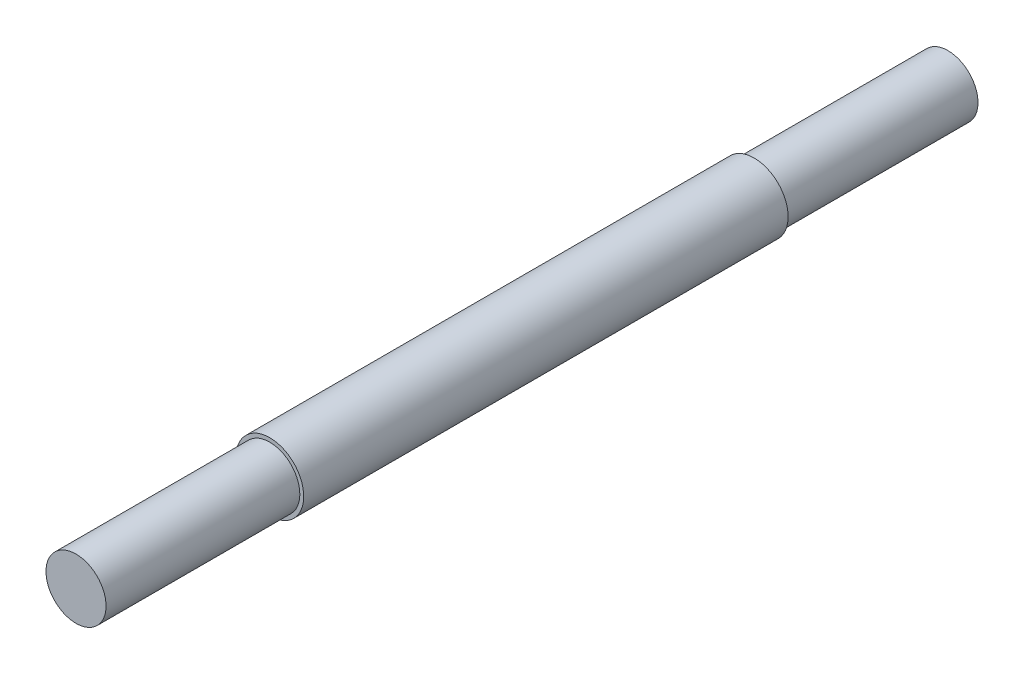
SolidWorks part; units mm, degrees
material "AISI 316 Annealed Stainless Steel Bar (SS)"
ref_plane "Front Plane" through (0, 0, 0) normal (0, 0, 1) x (1, 0, 0)
ref_plane "Top Plane" through (0, 0, 0) normal (0, 1, 0) x (1, 0, 0)
ref_plane "Right Plane" through (0, 0, 0) normal (1, 0, 0) x (0, 0, -1)
sketch "Sketch1" plane through (0, 0, 0) normal (1, 0, 0) x (0, 0, -1)
  line L0 (0, 0) -> (-22.5, 0)
  line L1 (-22.5, 0) -> (-22.5, 1.55)
  line L2 (-22.5, 1.55) -> (-12.5, 1.55)
  line L3 (-12.5, 1.55) -> (-12.5, 1.75)
  line L4 (-12.5, 1.75) -> (12.5, 1.75)
  line L5 (12.5, 1.75) -> (12.5, 1.55)
  line L6 (12.5, 1.55) -> (22.5, 1.55)
  line L7 (22.5, 1.55) -> (22.5, 0)
  line L8 (22.5, 0) -> (0, 0)
  dimension "D1" = 10
  dimension "D2" = 45
  dimension "D3" = 1.55
  dimension "D4" = 1.75
  dimension "D5" = 1.55
revolve "Revolve1" add sketch "Sketch1" angle 360 about L0
cosmetic thread "Cosmetic Thread1" parameters "D2"=3
cosmetic thread "Cosmetic Thread2" parameters "D2"=3
